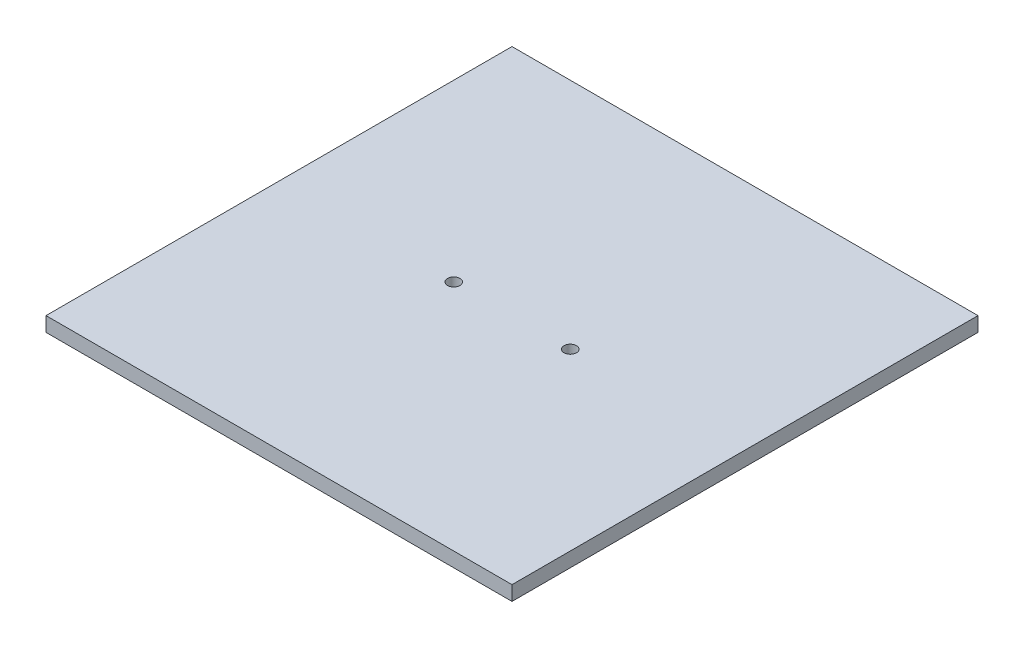
SolidWorks part; units mm, degrees
ref_plane "Front Plane" through (0, 0, 0) normal (0, 0, 1) x (1, 0, 0)
ref_plane "Top Plane" through (0, 0, 0) normal (0, 1, 0) x (1, 0, 0)
ref_plane "Right Plane" through (0, 0, 0) normal (1, 0, 0) x (0, 0, -1)
sketch "Sketch1" plane through (0, 0, 0) normal (0, 1, 0) x (1, 0, 0)
  line L1 (-50.8, -50.8) -> (50.8, -50.8)
  line L2 (-50.8, -50.8) -> (-50.8, 50.8)
  line L3 (-50.8, 50.8) -> (50.8, 50.8)
  line L4 (50.8, -50.8) -> (50.8, 50.8)
  line L5 (-50.8, -50.8) -> (50.8, 50.8) construction
  line L6 (-50.8, 50.8) -> (50.8, -50.8) construction
  point P0 (0, 0)
  dimension "D1" = 101.6
  dimension "D2" = 101.6
extrude "Boss-Extrude1" add sketch "Sketch1" along normal blind 3.175
hole_wizard "#6-32 Tapped Hole1" positions "Sketch2" profile "Sketch3" tap size "#6-32" standard "ANSI Inch" end condition through all
sketch "Sketch2" plane through (0, 3.175, 0) normal (0, 1, 0) x (1, 0, 0)
  line L0 (-12.7, 0) -> (12.7, 0) construction
  point P0 (-12.7, 0)
  point P2 (12.7, 0)
  point P37 (0, 0)
  point P38 (0, 0)
  dimension "D1" = 25.4
sketch "Sketch3" plane through (-12.7, 3.175, 0) normal (1, 0, 0) x (0, 0, 1)
  line L0 (0, 0) -> (0, 3.175)
  line L1 (0, 3.175) -> (1.3525, 3.175)
  line L2 (1.3525, 3.175) -> (1.3525, 0)
  line L5 (1.3525, 0) -> (0, 0)
  line L11 (0, -6.35) -> (0, 107.95) construction
  dimension "Thru Tap Drill Dia." = 2.7051
  dimension "Thru Tap Drill Depth" = 3.175
cosmetic thread "Hole Thread1" parameters "D2"=3.5052
cosmetic thread "Hole Thread2" parameters "D2"=3.5052
